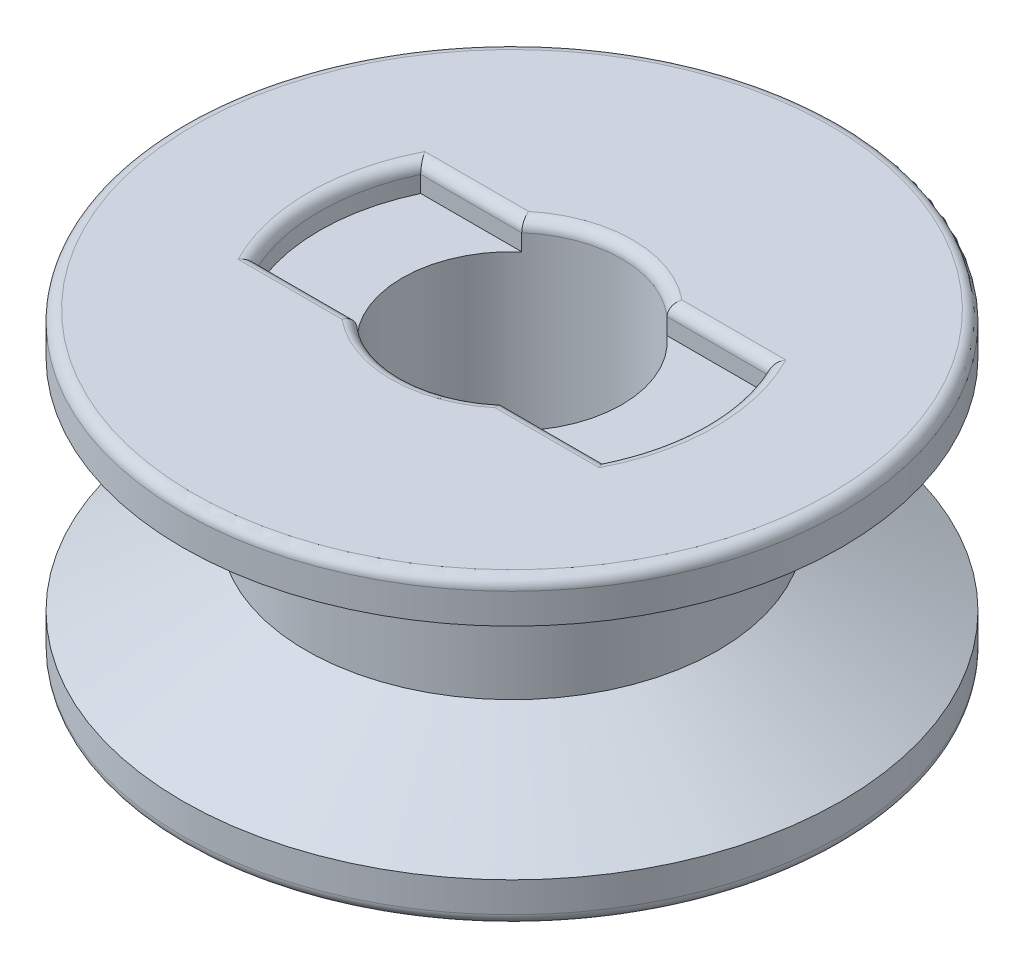
SolidWorks part; units mm, degrees
ref_plane "前视基准面" through (0, 0, 0) normal (0, 0, 1) x (1, 0, 0)
ref_plane "上视基准面" through (0, 0, 0) normal (0, 1, 0) x (1, 0, 0)
ref_plane "右视基准面" through (0, 0, 0) normal (1, 0, 0) x (0, 0, -1)
sketch "草图1" plane through (0, 0, 0) normal (0, 0, 1) x (1, 0, 0)
  line L0 (0, 0) -> (3.75, 0)
  line L1 (3.75, 0) -> (3.75, 0.75)
  line L2 (6, 2) -> (3.75, 0.75)
  line L3 (6, 2) -> (6, 2.75)
  line L4 (6, 2.75) -> (0, 2.75)
  line L5 (0, 2.75) -> (0, 0)
  dimension "D1" = 3.75
  dimension "D2" = 0.75
  dimension "D3" = 2.75
  dimension "D4" = 0.75
  dimension "D5" = 6
revolve "旋转1" add sketch "草图1" angle 360 about L5
mirror "镜向1" about plane through (0, 0, 0) normal (0, 1, 0) of "旋转1"
sketch "草图2" plane through (0, 2.75, 0) normal (0, 1, 0) x (1, 0, 0)
  line L1 (3.1623, 1.5) -> (-3.1623, 1.5)
  line L2 (3.1623, -1.5) -> (-3.1623, -1.5)
  line L4 (4.2376, 1.5) -> (-4.2376, -1.5) construction
  line L5 (4.2376, -1.5) -> (-4.2376, 1.5) construction
  arc A0 (-3.1623, 1.5) -> (-3.1623, -1.5) centre (0, 0) ccw
  arc A1 (3.1623, -1.5) -> (3.1623, 1.5) centre (0, 0) ccw
  dimension "D1" = 7
  dimension "D2" = 3
extrude "切除-拉伸1" cut sketch "草图2" against normal blind 0.5
mirror "镜向2" about plane through (0, 0, 0) normal (0, 1, 0) of "切除-拉伸1"
sketch "草图3" plane through (0, 2.75, 0) normal (0, 1, 0) x (1, 0, 0)
  circle A0 centre (0, 0) radius 2
  dimension "D1" = 4
extrude "切除-拉伸2" cut sketch "草图3" against normal through all
fillet "圆角1" radius 0.2 18 edges at (-3.5, -2.75, 0) (-2.2426, -2.75, -1.5) (0, -2.75, -2) (2.2426, -2.75, -1.5) (3.5, -2.75, 0) (2.2426, -2.75, 1.5) (0, -2.75, 2) (-2.2426, -2.75, 1.5) (-6, -2.75, 0) (-6, 2.75, 0) (3.5, 2.75, 0) (2.2426, 2.75, -1.5) (0, 2.75, -2) (-2.2426, 2.75, -1.5) (-3.5, 2.75, 0) (-2.2426, 2.75, 1.5) (0, 2.75, 2) (2.2426, 2.75, 1.5)
